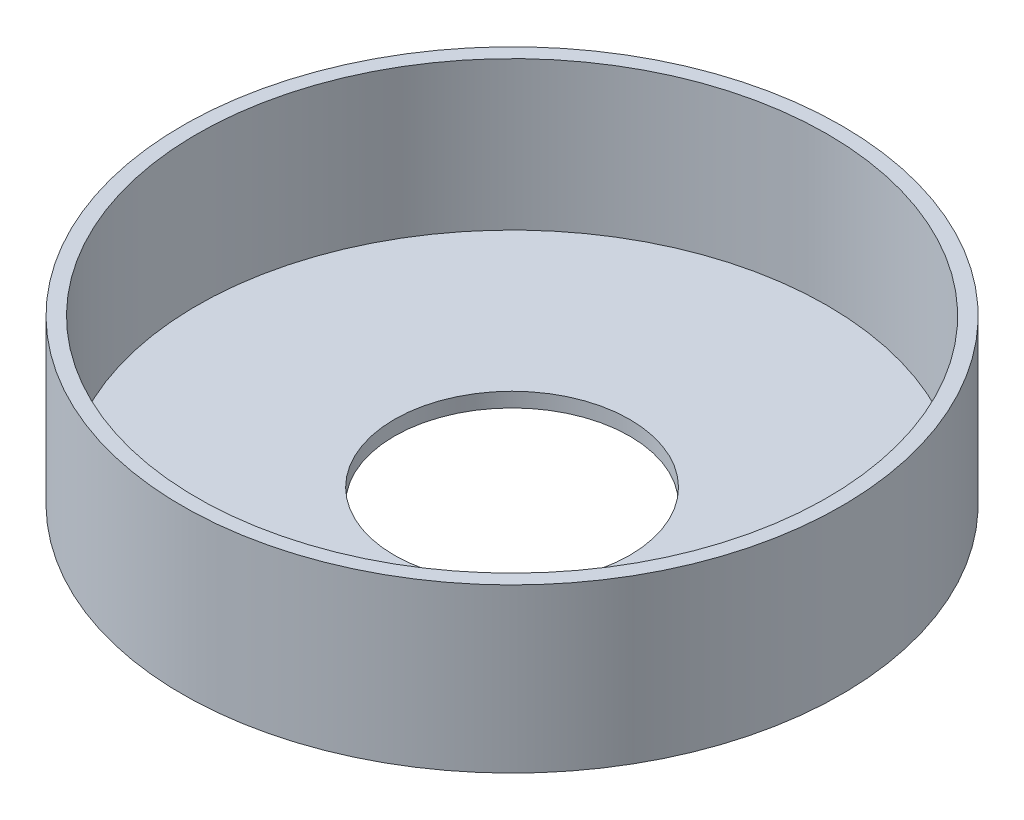
SolidWorks part; units mm, degrees
ref_plane "Alzado" through (0, 0, 0) normal (0, 0, 1) x (1, 0, 0)
ref_plane "Planta" through (0, 0, 0) normal (0, 1, 0) x (1, 0, 0)
ref_plane "Vista lateral" through (0, 0, 0) normal (1, 0, 0) x (0, 0, -1)
sketch "Croquis1" plane through (0, 0, 0) normal (0, 0, 1) x (1, 0, 0)
  line L0 (0, 0) -> (0, 33.8502) construction
  line L1 (3.25, 0) -> (9.1, 0)
  line L2 (9.1, 0) -> (9.1, 4.5)
  line L3 (3.25, 0.4) -> (8.7, 0.4)
  line L4 (8.7, 0.4) -> (8.7, 4.5)
  line L5 (8.7, 4.5) -> (9.1, 4.5)
  line L6 (3.25, 0.4) -> (3.25, 0)
  line L8 (0, 0.4) -> (8.7, 0.4) construction
  line L9 (0, 0) -> (9.1, 0) construction
  dimension "D2" = 18.2
  dimension "D3" = 4.5
  dimension "D4" = 6.5
  dimension "D1" = 0.4
revolve "Revolución1" add sketch "Croquis1" angle 360 about L0
